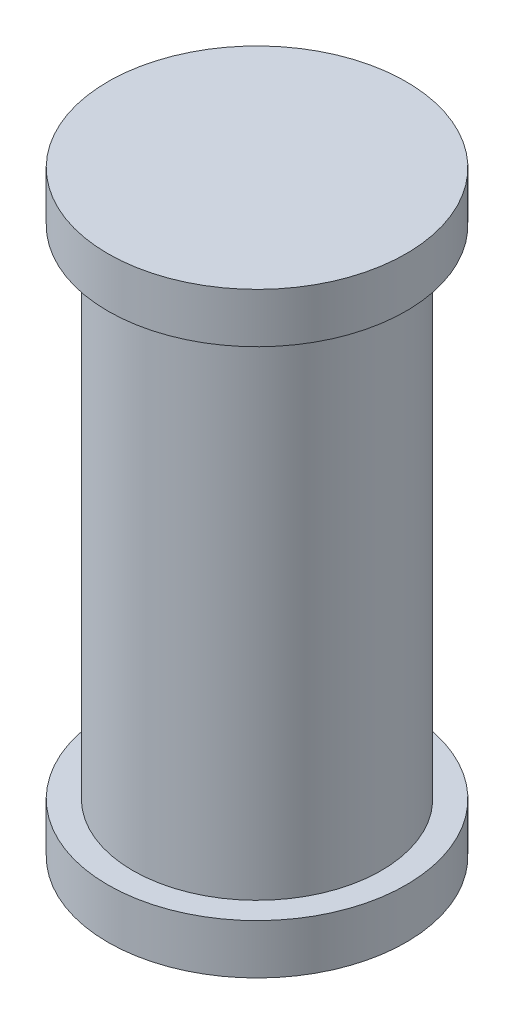
SolidWorks part; units mm, degrees
ref_plane "前基準面" through (0, 0, 0) normal (0, 0, 1) x (1, 0, 0)
ref_plane "上基準面" through (0, 0, 0) normal (0, 1, 0) x (1, 0, 0)
ref_plane "右基準面" through (0, 0, 0) normal (1, 0, 0) x (0, 0, -1)
sketch "草圖1" plane through (0, 0, 0) normal (0, 1, 0) x (1, 0, 0)
  circle A0 centre (0, 0) radius 30
  dimension "D1" = 60
extrude "填料-伸長1" add sketch "草圖1" along normal blind 10
sketch "草圖2" plane through (0, 10, 0) normal (0, 1, 0) x (1, 0, 0)
  circle A0 centre (0, 0) radius 25
  dimension "D1" = 50
extrude "填料-伸長2" add sketch "草圖2" along normal blind 100
sketch "草圖3" plane through (0, 110, 0) normal (0, 1, 0) x (1, 0, 0)
  circle A0 centre (0, 0) radius 30
  dimension "D1" = 60
extrude "填料-伸長3" add sketch "草圖3" along normal blind 10
